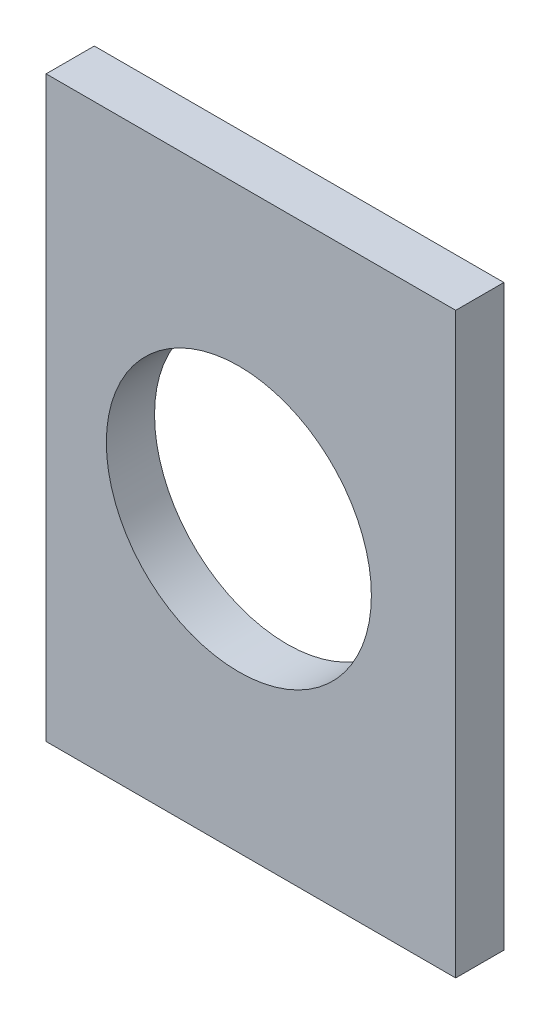
SolidWorks part; units mm, degrees
ref_plane "Front Plane" through (0, 0, 0) normal (0, 0, 1) x (1, 0, 0)
ref_plane "Top Plane" through (0, 0, 0) normal (0, 1, 0) x (1, 0, 0)
ref_plane "Right Plane" through (0, 0, 0) normal (1, 0, 0) x (0, 0, -1)
sketch "M5 floor attachment profile" plane through (0, 0, 0) normal (0, 0, 1) x (1, 0, 0)
  line L0 (94.5, -6) -> (103, -6)
  line L1 (103, -6) -> (103, 6)
  line L2 (103, 6) -> (94.5, 6)
  line L3 (94.5, 6) -> (94.5, -6)
  circle A0 centre (98.5, 0) radius 2.75
extrude "M5 floor attachment" add sketch "M5 floor attachment profile" along normal blind 1
